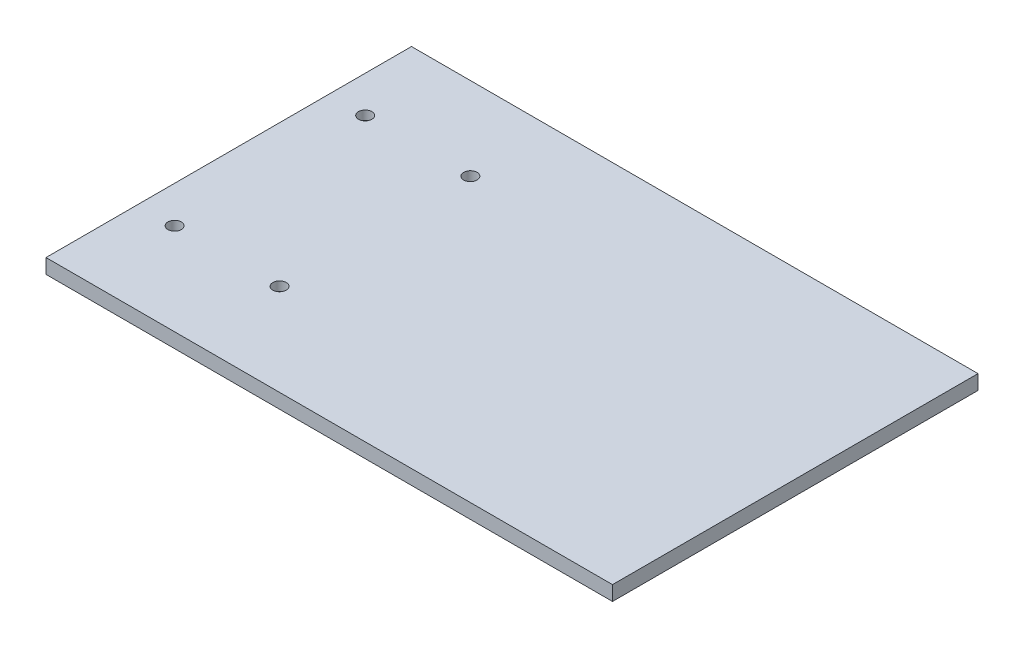
SolidWorks part; units mm, degrees
material "Maple"
ref_plane "Front Plane" through (0, 0, 0) normal (0, 0, 1) x (1, 0, 0)
ref_plane "Top Plane" through (0, 0, 0) normal (0, 1, 0) x (1, 0, 0)
ref_plane "Right Plane" through (0, 0, 0) normal (1, 0, 0) x (0, 0, -1)
sketch "Sketch1" plane through (0, 0, 0) normal (0, 1, 0) x (1, 0, 0)
  line L0 (-232.5, 150) -> (232.5, 150)
  line L1 (-232.5, 150) -> (-232.5, -150)
  line L2 (232.5, 150) -> (232.5, -150)
  line L3 (-232.5, -150) -> (232.5, -150)
  line L4 (-232.5, 150) -> (232.5, -150) construction
  line L5 (232.5, 150) -> (-232.5, -150) construction
  point P1 (0, 0)
  dimension "D1" = 300
  dimension "D2" = 465
extrude "Boss-Extrude1" add sketch "Sketch1" along normal blind 12
hole_wizard "CSK for M10 Countersunk Flat Head Screw1" positions "Sketch3" profile "Sketch2" countersink size "M10" standard "ISO"
sketch "Sketch3" plane through (0, 0, 0) normal (0, -1, 0) x (-1, 0, 0)
  point P23 (116.1691, -74.6127)
  point P25 (202.3044, -74.6127)
  point P27 (202.5, 82)
  point P29 (116.1691, 82)
sketch "Sketch2" plane through (-116.1691, 0, 74.6127) normal (1, 0, 0) x (0, 0, -1)
  line L0 (0, 0) -> (0, 23.3077)
  line L1 (0, 23.3077) -> (5.5, 20.003)
  line L2 (5.5, 20.003) -> (5.5, 4.5)
  line L3 (5.5, 4.5) -> (10, 0)
  line L5 (10, 0) -> (0, 0)
  line L6 (-5.5, 4.5) -> (-10, 0) construction
  line L10 (0, 23.3077) -> (-5.5, 20.003) construction
  line L11 (0, -6.35) -> (0, 107.95) construction
  dimension "Hole Dia." = 11
  dimension "Hole Depth" = 20.003
  dimension "Near C'Sink Dia." = 20
  dimension "Near C'Sink Angle" = 90
  dimension "Drill Angle" = 118
